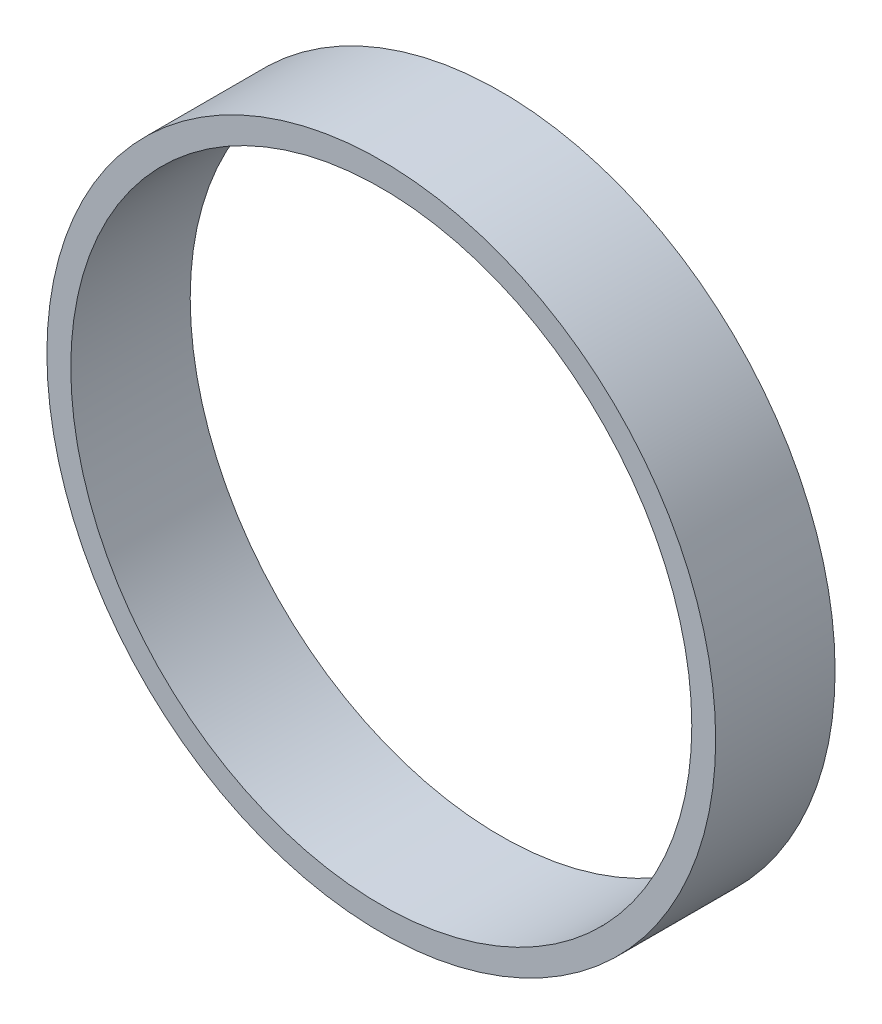
SolidWorks part; units mm, degrees
material "Caoutchouc silicone"
ref_plane "Plan de face" through (0, 0, 0) normal (0, 0, 1) x (1, 0, 0)
ref_plane "Plan de dessus" through (0, 0, 0) normal (0, 1, 0) x (1, 0, 0)
ref_plane "Plan de droite" through (0, 0, 0) normal (1, 0, 0) x (0, 0, -1)
sketch "Esquisse1" plane through (0, 0, 0) normal (0, 0, 1) x (1, 0, 0)
  circle A0 centre (0, 0) radius 28
  circle A1 centre (0, 0) radius 26
extrude "Boss.-Extru.1" add sketch "Esquisse1" along normal blind 10
